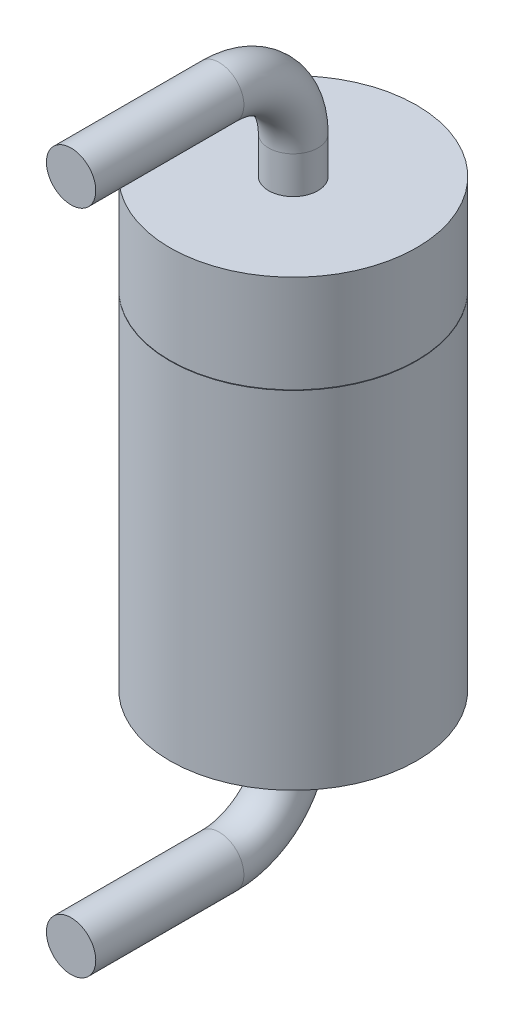
SolidWorks part; units mm, degrees
ref_plane "前视基准面" through (0, 0, 0) normal (0, 0, 1) x (1, 0, 0)
ref_plane "上视基准面" through (0, 0, 0) normal (0, 1, 0) x (1, 0, 0)
ref_plane "右视基准面" through (0, 0, 0) normal (1, 0, 0) x (0, 0, -1)
sketch "草图1" plane through (0, 0, 0) normal (0, 1, 0) x (1, 0, 0)
  circle A0 centre (0, 0) radius 2.5
  dimension "D1" = 5
extrude "凸台-拉伸1" add sketch "草图1" along normal blind 9
ref_axis "基准轴1" through (0, 9.45, 0) along (0, -1, 0)
sketch "草图4" plane through (0, 0, 0) normal (0, 0, 1) x (1, 0, 0)
  line L0 (-2.5, 9) -> (-2.5, 0) construction
  line L1 (-3.3764, 7.0239) -> (-2.3, 7.0239)
  line L2 (-3.3764, 7.0239) -> (-3.3764, 6.7739)
  line L3 (-3.3764, 6.7739) -> (-2.3, 6.7739)
  line L4 (-2.3, 7.0239) -> (-2.3, 6.7739)
  dimension "D1" = 0.25
  dimension "D2" = 0.2
revolve "切除-旋转1" cut sketch "草图4" angle 360 about axis through (0, 9.45, 0) along (0, -1, 0)
sketch "草图5" plane through (0, 6.7739, 0) normal (0, 1, 0) x (1, 0, 0)
  circle A0 centre (0, 0) radius 2.5
  dimension "D1" = 5
extrude "凸台-拉伸3" add sketch "草图5" along normal blind 0.24
sketch "草图6" plane through (0, 0, 0) normal (0, -1, 0) x (1, 0, 0)
  line L0 (0, -2.75) -> (0, 2.75) construction
  circle A0 centre (0, 0) radius 0.5
  dimension "D1" = 1
sketch "草图7" plane through (0, 0, 0) normal (1, 0, 0) x (0, 0, -1)
  line L0 (-2.5, 9) -> (-3.1501, 9) construction
  line L1 (-3.1501, 9) -> (-3.1501, 0) construction
  line L3 (-3.1501, 4.5) -> (3.2587, 4.5) construction
  line L4 (-4.8569, -2.25) -> (4.5535, -2.25) construction
  line L5 (-4.5, -2.75) -> (-1.5, -2.75)
  line L6 (0.5, 0) -> (0.5, -0.75)
  line L7 (-0.5, 0) -> (0.5, 0) construction
  arc A0 (0.5, -0.75) -> (-1.5, -2.75) centre (-1.5, -0.75) cw
  dimension "D4" = 2
  dimension "D1" = 6.75
  dimension "D2" = 1
  dimension "D3" = 2
sweep "扫描1" add profiles "草图6" path "草图7"
ref_plane "基准面1" through (0, 4.5, 0) normal (0, 1, 0) x (-1, 0, 0)
mirror "镜向1" about plane through (0, 4.5, 0) normal (0, 1, 0) of "扫描1"
